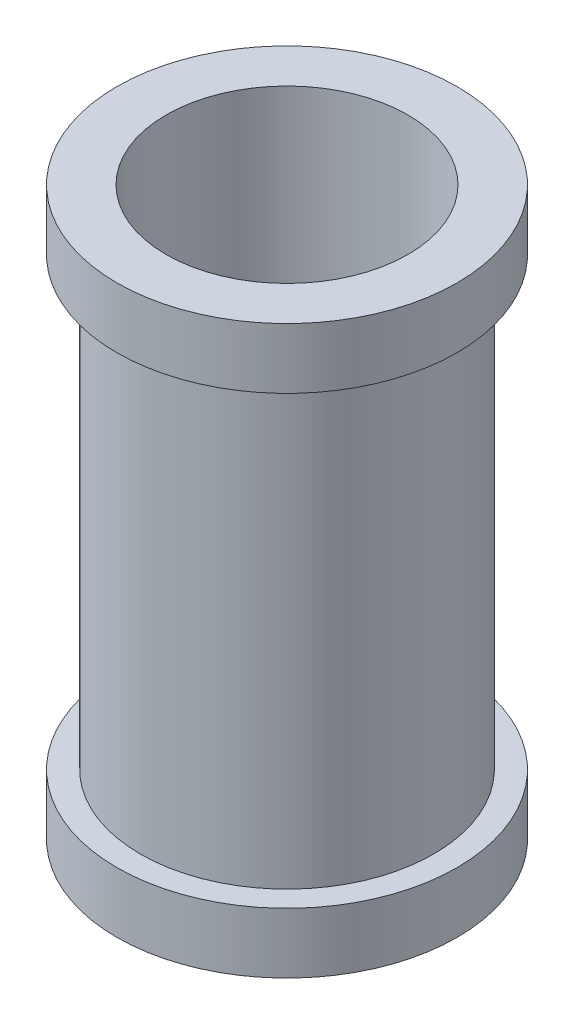
SolidWorks part; units mm, degrees
ref_plane "Front Plane" through (0, 0, 0) normal (0, 0, 1) x (1, 0, 0)
ref_plane "Top Plane" through (0, 0, 0) normal (0, 1, 0) x (1, 0, 0)
ref_plane "Right Plane" through (0, 0, 0) normal (1, 0, 0) x (0, 0, -1)
sketch "Sketch3" plane through (0, 0, 0) normal (0, 1, 0) x (1, 0, 0)
  circle A0 centre (0, 0) radius 28.575
extrude "Boss-Extrude2" add sketch "Sketch3" along normal blind 10.16
sketch "Sketch4" plane through (0, 10.16, 0) normal (0, 1, 0) x (1, 0, 0)
  circle A1 centre (0, 0) radius 24.638
extrude "Boss-Extrude3" add sketch "Sketch4" along normal blind 85.09
sketch "Sketch5" plane through (0, 95.25, 0) normal (0, 1, 0) x (1, 0, 0)
  circle A0 centre (0, 0) radius 28.575
extrude "Boss-Extrude4" add sketch "Sketch5" against normal blind 10.16
sketch "Sketch6" plane through (0, 95.25, 0) normal (0, 1, 0) x (1, 0, 0)
  circle A1 centre (0, 0) radius 20.32
extrude "Cut-Extrude1" cut sketch "Sketch6" against normal blind 104.14
